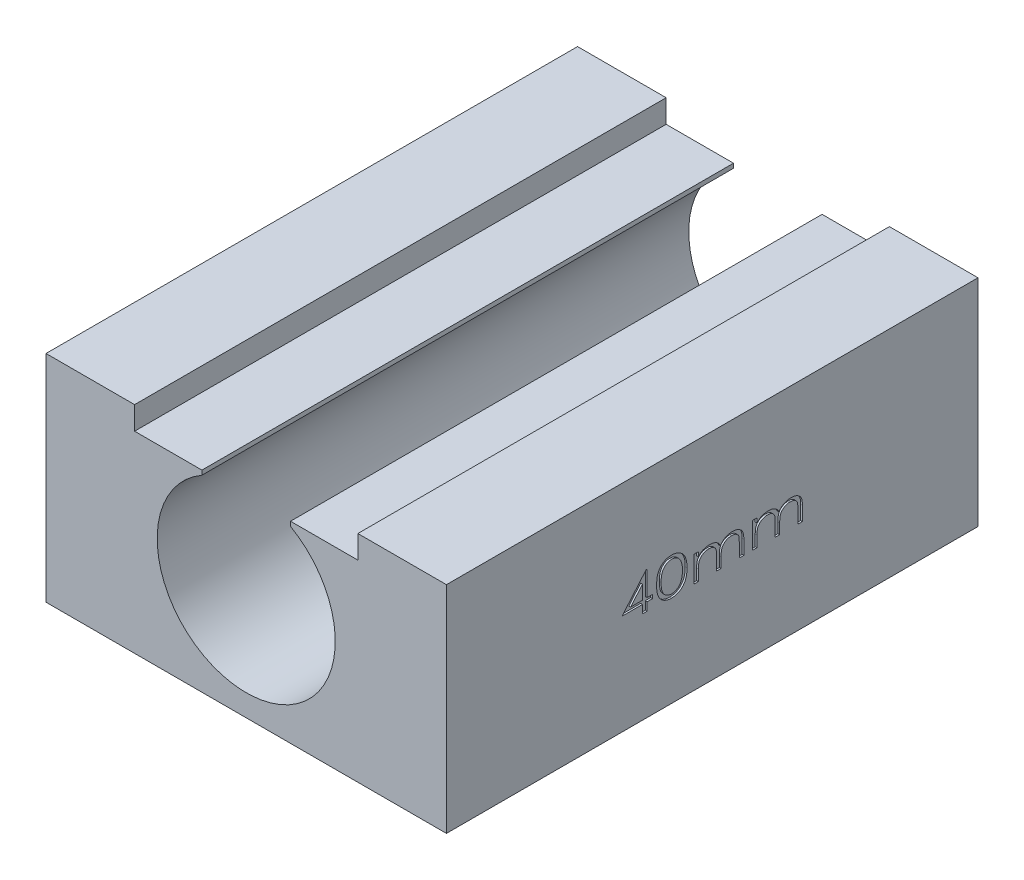
SolidWorks part; units mm, degrees
ref_plane "Front Plane" through (0, 0, 0) normal (0, 0, 1) x (1, 0, 0)
ref_plane "Top Plane" through (0, 0, 0) normal (0, 1, 0) x (1, 0, 0)
ref_plane "Right Plane" through (0, 0, 0) normal (1, 0, 0) x (0, 0, -1)
sketch "Sketch1" plane through (0, 0, 0) normal (0, 0, 1) x (1, 0, 0)
  line L0 (0, 0) -> (0, 28.6359) construction
  line L1 (0, 28.6359) -> (-10, 18.6359)
  line L2 (0, 28.6359) -> (10, 18.6359)
  line L3 (-10, 18.6359) -> (-25, 18.6359)
  line L4 (-25, 18.6359) -> (-25, 38.6359)
  line L5 (-25, 38.6359) -> (25, 38.6359)
  line L6 (25, 38.6359) -> (25, 18.6359)
  line L7 (25, 18.6359) -> (10, 18.6359)
  line L8 (-45.2, 23.6359) -> (-45.2, -25)
  line L9 (-45.2, -25) -> (45.2, -25)
  line L10 (45.2, -25) -> (45.2, 23.6359)
  line L11 (45.2, 23.6359) -> (25.2, 23.6359)
  line L12 (25.2, 23.6359) -> (25.2, 18.4359)
  line L13 (-25.2, 18.4359) -> (-10, 18.4359)
  line L14 (-45.2, 23.6359) -> (-25.2, 23.6359)
  line L15 (-25.2, 23.6359) -> (-25.2, 18.4359)
  line L16 (25.2, 18.4359) -> (10, 18.4359)
  line L17 (-10, 18.4359) -> (-10, 17.4359)
  line L18 (10, 18.4359) -> (10, 17.4359)
  circle A0 centre (0, 0) radius 20.1
  dimension "D12" = 40.2
  dimension "D1" = 45
  dimension "D2" = 10
  dimension "D3" = 20
  dimension "D4" = 50
  dimension "D5" = 25
  dimension "D6" = 5
  dimension "D7" = 0.2
  dimension "D8" = 0.2
  dimension "D9" = 5
  dimension "D10" = 20
  dimension "D11" = 20
  dimension "D13" = 25
  dimension "D14" = 0.2
  dimension "D15" = 0.2
  dimension "D16" = 1
extrude "Boss-Extrude1" add sketch "Sketch1" along normal blind 120 contours A0 L17 L13 L15 L14 L8 L9 L10 L11 L12 L16 L18
sketch "Sketch2" plane through (45.2, 0, 0) normal (1, 0, 0) x (0, 0, -1)
  text T0 "40mm" font "Century Gothic" height 8
extrude "Cut-Extrude1" cut sketch "Sketch2" against normal blind 0.4
